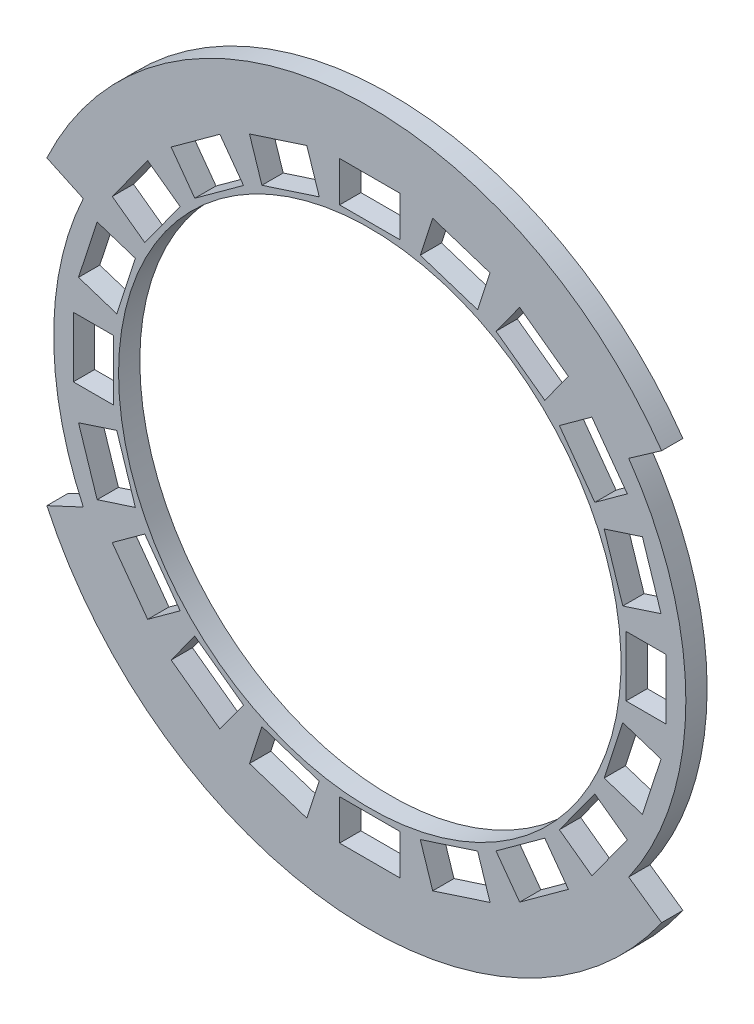
SolidWorks part; units mm, degrees
material "6061-T6 (SS)"
ref_plane "Front Plane" through (0, 0, 0) normal (0, 0, 1) x (1, 0, 0)
ref_plane "Top Plane" through (0, 0, 0) normal (0, 1, 0) x (1, 0, 0)
ref_plane "Right Plane" through (0, 0, 0) normal (1, 0, 0) x (0, 0, -1)
sketch "Sketch1" plane through (0, 0, 0) normal (0, 0, 1) x (1, 0, 0)
  line L0 (-85.5247, 39.8808) -> (-96.4004, 44.9522) construction
  line L1 (87.1299, 61.009) -> (77.3001, 54.1261) construction
  line L2 (-85.5247, 39.8808) -> (-96.4004, 44.9522)
  line L3 (87.1299, 61.009) -> (77.3001, 54.1261)
  circle A0 centre (0, 0) radius 75 construction
  circle A1 centre (0, 0) radius 75
  circle A2 centre (0, 0) radius 106.366 construction
  circle A3 centre (0, 0) radius 106.366 construction
  arc A4 (-96.4004, 44.9522) -> (87.1299, 61.009) centre (0, 0) cw
  circle A5 centre (0, 0) radius 94.366 construction
  circle A6 centre (0, 0) radius 94.366 construction
  arc A7 (-85.5247, 39.8808) -> (77.3001, 54.1261) centre (0, 0) ccw
extrude "Boss-Extrude1" add sketch "Sketch1" along normal up to surface (6.35 mm away)
mirror "Mirror1" about plane through (0, 0, 0) normal (0, 1, 0) of "Boss-Extrude1"
sketch "Sketch2" plane through (0, 0, 6.35) normal (0, 0, 1) x (1, 0, 0)
  line L0 (0, 82.5) -> (0, 0) construction
  line L1 (-9, 88.5) -> (9, 88.5)
  line L2 (-9, 88.5) -> (-9, 76.5)
  line L3 (-9, 76.5) -> (9, 76.5)
  line L4 (9, 88.5) -> (9, 76.5)
  line L5 (-9, 88.5) -> (9, 76.5) construction
  line L6 (-9, 76.5) -> (9, 88.5) construction
  arc A0 (-85.5247, 39.8808) -> (77.3001, 54.1261) centre (0, 0) cw construction
  arc A1 (77.3001, -54.1261) -> (77.3001, 54.1261) centre (0, 0) ccw construction
  circle A2 centre (0, 0) radius 75 construction
  circle A3 centre (0, 0) radius 75 construction
  point P10 (0, 82.5)
  point P17 (0, 75)
  dimension "D1" = 12
  dimension "D2" = 18
  dimension "D3" = 1.5
extrude "Cut-Extrude1" cut sketch "Sketch2" against normal through all
pattern_circular "CirPattern1" count 20 over 360 about axis through (0, 0, 0) along (0, 0, 1) of "Cut-Extrude1"
